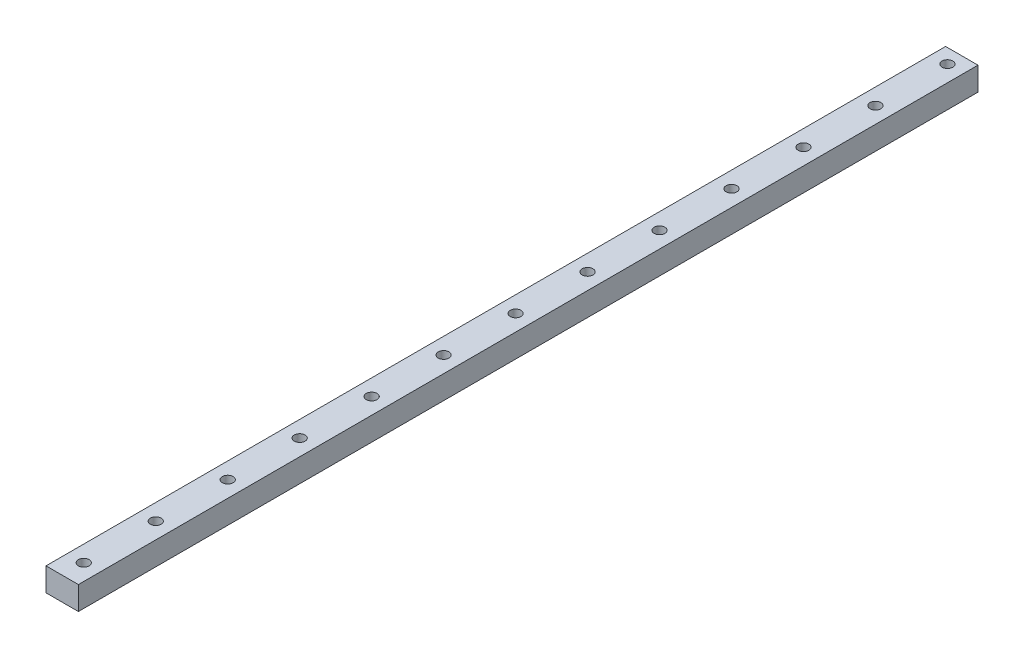
SolidWorks part; units mm, degrees
ref_plane "前视基准面" through (0, 0, 0) normal (0, 0, 1) x (1, 0, 0)
ref_plane "上视基准面" through (0, 0, 0) normal (0, 1, 0) x (1, 0, 0)
ref_plane "右视基准面" through (0, 0, 0) normal (1, 0, 0) x (0, 0, -1)
other "Configuration Table"
sketch "草图1" plane through (0, 0, 0) normal (0, 0, 1) x (1, 0, 0)
  line L1 (-4.5, 3.25) -> (4.5, 3.25)
  line L2 (-4.5, 3.25) -> (-4.5, -3.25)
  line L3 (-4.5, -3.25) -> (4.5, -3.25)
  line L4 (4.5, 3.25) -> (4.5, -3.25)
  line L5 (-4.5, 3.25) -> (4.5, -3.25) construction
  line L6 (-4.5, -3.25) -> (4.5, 3.25) construction
  point P0 (0, 0)
  dimension "D1" = 9
  dimension "D2" = 6.5
extrude "凸台-拉伸1" add sketch "草图1" along normal blind 250
sketch "草图2" plane through (0, 3.25, 0) normal (0, 1, 0) x (1, 0, 0)
  line L0 (4.5, 0) -> (-4.5, 0) construction
  circle A0 centre (0, -4) radius 1.5
  circle A1 centre (0, -24) radius 1.5
  circle A2 centre (0, -44) radius 1.5
  circle A3 centre (0, -64) radius 1.5
  circle A4 centre (0, -84) radius 1.5
  circle A5 centre (0, -104) radius 1.5
  circle A6 centre (0, -124) radius 1.5
  circle A7 centre (0, -144) radius 1.5
  circle A8 centre (0, -164) radius 1.5
  circle A9 centre (0, -184) radius 1.5
  circle A10 centre (0, -204) radius 1.5
  circle A11 centre (0, -224) radius 1.5
  circle A12 centre (0, -244) radius 1.5
  dimension "D1" = 3
  dimension "D2" = 4
  dimension "D3" = 13
extrude "切除-拉伸1" cut sketch "草图2" against normal blind 250
